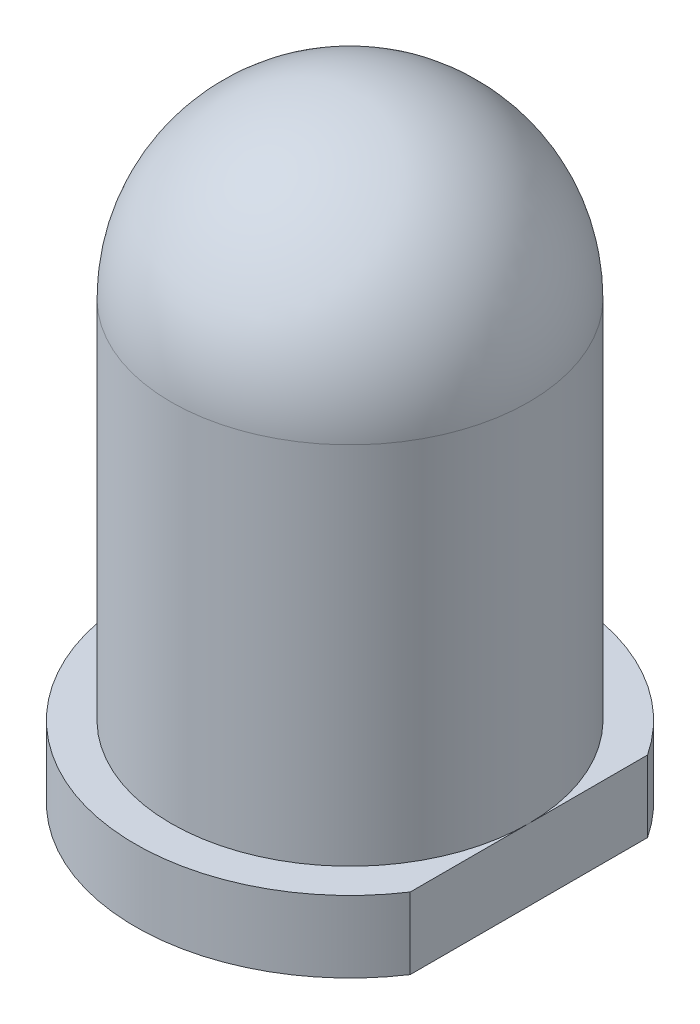
SolidWorks part; units mm, degrees
material "Пластик (бел)"
ref_plane "Спереди" through (0, 0, 0) normal (0, 0, 1) x (1, 0, 0)
ref_plane "Сверху" through (0, 0, 0) normal (0, 1, 0) x (1, 0, 0)
ref_plane "Справа" through (0, 0, 0) normal (1, 0, 0) x (0, 0, -1)
sketch "Эскиз1" plane through (0, 0, 0) normal (0, 0, 1) x (1, 0, 0)
  line L0 (0, 0) -> (0, 8.6)
  line L1 (0, 0) -> (0, -7.1252) construction
  line L2 (-2.5, 6.1) -> (-2.5, 0)
  line L3 (-2.5, 0) -> (0, 0)
  arc A0 (0, 8.6) -> (-2.5, 6.1) centre (0, 6.1) ccw
  dimension "D1" = 5
  dimension "D2" = 8.6
revolve "Повернуть1" add sketch "Эскиз1" angle 360 about L1
sketch "Эскиз2" plane through (0, 0, 0) normal (0, -1, 0) x (1, 0, 0)
  circle A0 centre (0, 0) radius 3
  dimension "D1" = 6
extrude "Бобышка-Вытянуть1" add sketch "Эскиз2" against normal blind 1
sketch "Эскиз3" plane through (0, 0, 0) normal (0, 1, 0) x (1, 0, 0)
  line L0 (2.5, 1.6583) -> (2.5, -1.6583)
  circle A0 centre (0, 0) radius 3 construction
  circle A1 centre (0, 0) radius 3
  circle A2 centre (0, 0) radius 2.5 construction
extrude "Вырез-Вытянуть1" cut sketch "Эскиз3" along normal through all contours L0 A1
